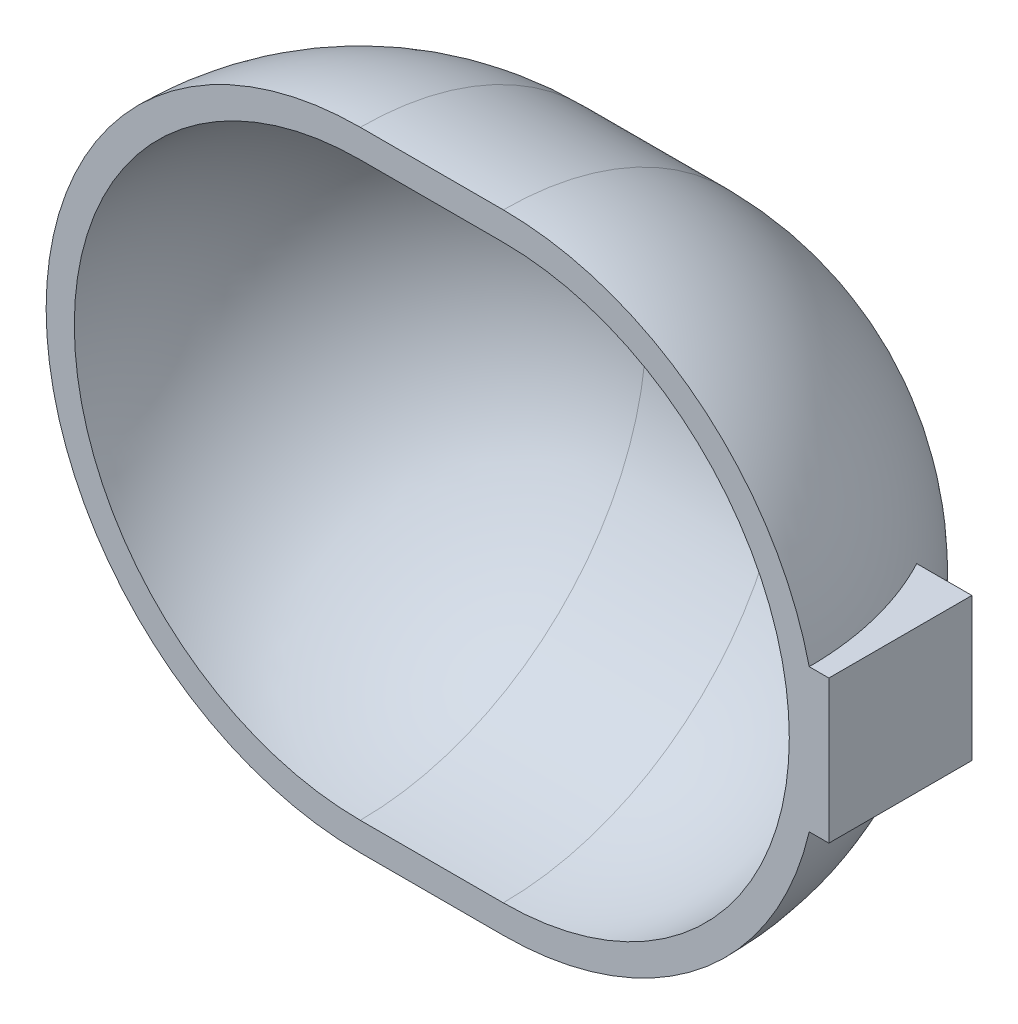
SolidWorks part; units mm, degrees
material "Oak"
ref_plane "Front Plane" through (0, 0, 0) normal (0, 0, 1) x (1, 0, 0)
ref_plane "Top Plane" through (0, 0, 0) normal (0, 1, 0) x (1, 0, 0)
ref_plane "Right Plane" through (0, 0, 0) normal (1, 0, 0) x (0, 0, -1)
sketch "Sketch2" plane through (0, 0, 0) normal (0, 0, 1) x (1, 0, 0)
  line L0 (-279, 0) -> (279, 0)
  line L1 (279, 0) -> (533, 0)
  line L2 (533, 0) -> (1091, 0)
  line L3 (533, 0) -> (533, -558) construction
  line L4 (279, 0) -> (279, -558) construction
  line L5 (279, -558) -> (533, -558)
  arc A0 (533, -558) -> (1091, 0) centre (533, 0) ccw
  arc A1 (-279, 0) -> (279, -558) centre (279, 0) ccw
  point P4 (0, 0)
  dimension "D1" = 558
  dimension "D2" = 254
  dimension "D3" = 558
revolve "Revolve1" add sketch "Sketch2" angle 180 about L2
shell "Shell1" thickness 50
sketch "Sketch4" plane through (0, 0, 0) normal (0, 0, 1) x (1, 0, 0)
  line L0 (1091, 0) -> (1111.26, 0) construction
  arc A0 (533, -558) -> (533, 558) centre (533, 0) ccw construction
  dimension "D1" = 20.26
ref_plane "Plane1" through (1111.26, 0, 0) normal (1, 0, 0) x (0, 0, -1)
sketch "Sketch5" plane through (1111.26, 0, 0) normal (1, 0, 0) x (0, 0, -1)
  line L1 (0, -127) -> (254, -127)
  line L2 (0, -127) -> (0, 127)
  line L3 (0, 127) -> (254, 127)
  line L4 (254, -127) -> (254, 127)
  line L5 (0, -127) -> (254, 127) construction
  line L6 (0, 127) -> (254, -127) construction
  point P0 (127, 0)
  point P5 (0, 0)
  dimension "D1" = 254
  dimension "D2" = 254
extrude "Boss-Extrude2" add sketch "Sketch5" against normal up to surface (34.9047 mm away)
